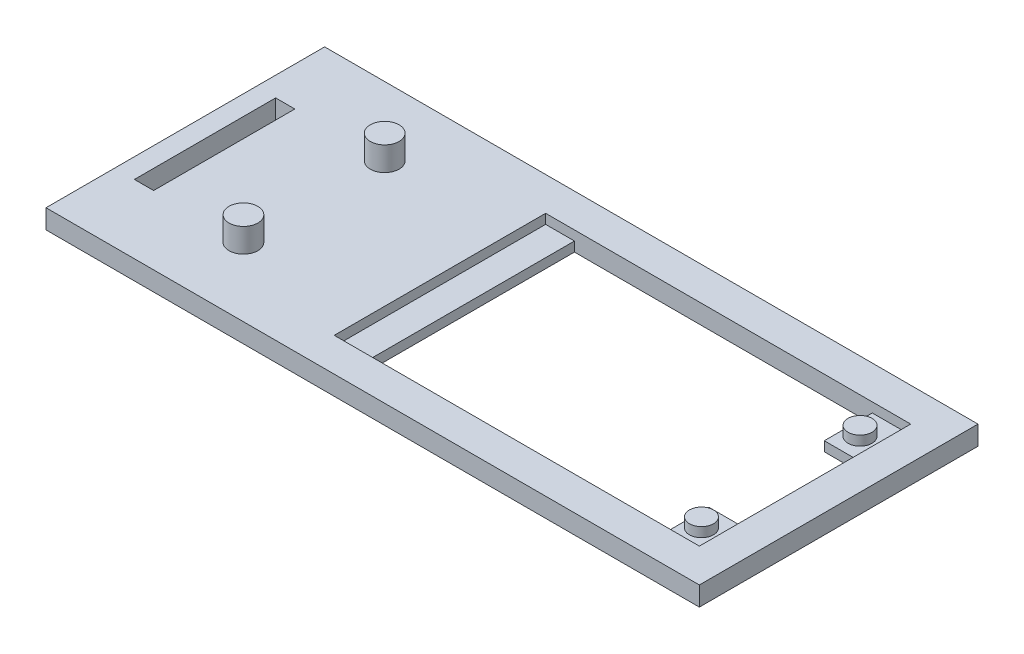
SolidWorks part; units mm, degrees
ref_plane "Front Plane" through (0, 0, 0) normal (0, 0, 1) x (1, 0, 0)
ref_plane "Top Plane" through (0, 0, 0) normal (0, 1, 0) x (1, 0, 0)
ref_plane "Right Plane" through (0, 0, 0) normal (1, 0, 0) x (0, 0, -1)
sketch "Sketch1" plane through (0, 0, 0) normal (0, 1, 0) x (1, 0, 0)
  line L1 (-27.5556, 17.0556) -> (40.4444, 17.0556)
  line L2 (-27.5556, 17.0556) -> (-27.5556, -11.9444)
  line L3 (-27.5556, -11.9444) -> (40.4444, -11.9444)
  line L4 (40.4444, 17.0556) -> (40.4444, -11.9444)
  dimension "D1" = 68
  dimension "D2" = 29
extrude "base" add sketch "Sketch1" along normal blind 2
sketch "Sketch2" plane through (0, 2, 0) normal (0, 1, 0) x (1, 0, 0)
  line L0 (-27.5556, -11.9444) -> (40.4444, -11.9444) construction
  line L1 (-27.5556, 17.0556) -> (-27.5556, -11.9444) construction
  circle A0 centre (-14.1556, -4.7944) radius 1.5
  dimension "D1" = 3
  dimension "D2" = 7.15
  dimension "D3" = 13.4
extrude "left peg" add sketch "Sketch2" along normal blind 2.5
sketch "Sketch3" plane through (0, 2, 0) normal (0, 1, 0) x (1, 0, 0)
  line L1 (-27.5556, 17.0556) -> (-27.5556, -11.9444) construction
  circle A0 centre (-14.1556, 9.9056) radius 1.5
  circle A1 centre (-14.1556, -4.7944) radius 1.5 construction
  dimension "D1" = 3
  dimension "D2" = 13.4
  dimension "D3" = 14.7
extrude "right peg" add sketch "Sketch3" along normal blind 2.5
sketch "Sketch4" plane through (0, 2, 0) normal (0, 1, 0) x (1, 0, 0)
  line L0 (40.4444, 17.0556) -> (-27.5556, 17.0556) construction
  line L1 (-25.5056, 9.9056) -> (-23.5056, 9.9056)
  line L2 (-25.5056, 9.9056) -> (-25.5056, -4.7944)
  line L3 (-25.5056, -4.7944) -> (-23.5056, -4.7944)
  line L4 (-23.5056, 9.9056) -> (-23.5056, -4.7944)
  circle A0 centre (-14.1556, -4.7944) radius 1.5 construction
  dimension "D1" = 2
  dimension "D2" = 14.7
  dimension "D3" = 7.15
  dimension "D4" = 9.35
extrude "accel wire hole" cut sketch "Sketch4" against normal blind 2.5
sketch "Sketch5" plane through (0, 2, 0) normal (0, 1, 0) x (1, 0, 0)
  line L0 (40.4444, 17.0556) -> (-27.5556, 17.0556) construction
  line L1 (-1.0556, 13.5556) -> (36.9444, 13.5556)
  line L2 (-1.0556, 13.5556) -> (-1.0556, -8.4444)
  line L3 (-1.0556, -8.4444) -> (36.9444, -8.4444)
  line L4 (36.9444, 13.5556) -> (36.9444, -8.4444)
  line L5 (40.4444, -11.9444) -> (40.4444, 17.0556) construction
  dimension "D1" = 38
  dimension "D2" = 22
  dimension "D3" = 3.5
  dimension "D4" = 3.5
extrude "outer cut" cut sketch "Sketch5" against normal blind 1
sketch "Sketch6" plane through (0, 1, 0) normal (0, 1, 0) x (1, 0, 0)
  line L0 (36.9444, 13.5556) -> (-1.0556, 13.5556) construction
  line L1 (1.9444, 13.5556) -> (32.9444, 13.5556)
  line L2 (1.9444, 13.5556) -> (1.9444, -8.4444)
  line L3 (1.9444, -8.4444) -> (32.9444, -8.4444)
  line L4 (32.9444, 13.5556) -> (32.9444, -8.4444)
  line L5 (-1.0556, -8.4444) -> (36.9444, -8.4444) construction
  line L6 (-1.0556, 13.5556) -> (-1.0556, -8.4444) construction
  line L7 (36.9444, -8.4444) -> (36.9444, 13.5556) construction
  dimension "D1" = 3
  dimension "D2" = 4
extrude "inner cut" cut sketch "Sketch6" against normal blind 1
sketch "Sketch7" plane through (0, 1, 0) normal (0, 1, 0) x (1, 0, 0)
  line L0 (36.9444, -8.4444) -> (36.9444, 13.5556) construction
  line L1 (32.9444, 8.5556) -> (36.9444, 8.5556)
  line L2 (32.9444, 8.5556) -> (32.9444, -3.4444)
  line L3 (32.9444, -3.4444) -> (36.9444, -3.4444)
  line L4 (36.9444, 8.5556) -> (36.9444, -3.4444)
  line L5 (32.9444, -8.4444) -> (32.9444, 13.5556) construction
  line L6 (36.9444, 13.5556) -> (32.9444, 13.5556) construction
  line L7 (32.9444, -8.4444) -> (36.9444, -8.4444) construction
  dimension "D1" = 5
  dimension "D2" = 5
extrude "between peg cut" cut sketch "Sketch7" against normal blind 1
sketch "Sketch8" plane through (0, 1, 0) normal (0, 1, 0) x (1, 0, 0)
  line L0 (36.9444, 13.5556) -> (32.9444, 13.5556) construction
  circle A0 centre (34.4149, 10.8056) radius 1.25
  circle A1 centre (34.4149, -5.6944) radius 1.25
  point P4 (0, 0)
  dimension "D1" = 2.5
  dimension "D2" = 2.5
  dimension "D3" = 16.5
  dimension "D4" = 2.75
extrude "pegs" add sketch "Sketch8" along normal blind 1
